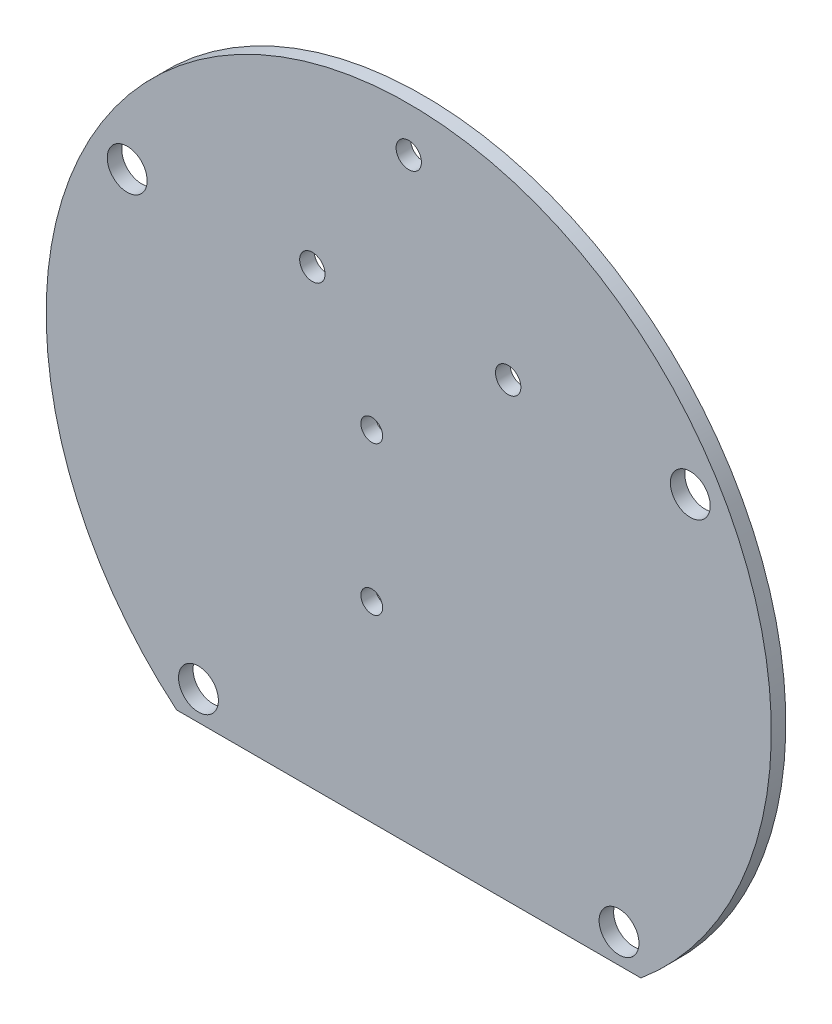
SolidWorks part; units mm, degrees
ref_plane "Plano frontal" through (0, 0, 0) normal (0, 0, 1) x (1, 0, 0)
ref_plane "Plano superior" through (0, 0, 0) normal (0, 1, 0) x (1, 0, 0)
ref_plane "Plano direito" through (0, 0, 0) normal (1, 0, 0) x (0, 0, -1)
sketch "Esboço1" plane through (0, 0, 0) normal (0, 0, 1) x (1, 0, 0)
  circle A0 centre (0, 0) radius 50
  dimension "D1" = 100
extrude "Ressalto-extrusão1" add sketch "Esboço1" along normal blind 2
sketch "Esboço2" plane through (0, 0, 2) normal (0, 0, 1) x (1, 0, 0)
  line L0 (0, 0) -> (0, 68.6386) construction
  line L1 (-61.9657, 0) -> (66.0984, 0) construction
  line L2 (-61.9657, -34.4093) -> (66.0984, -34.4093) construction
  circle A4 centre (-29, -34.4093) radius 2.75
  circle A5 centre (29, -34.4093) radius 2.75
  circle A6 centre (-38.8242, 22.7526) radius 2.75
  circle A7 centre (38.8242, 22.7526) radius 2.75
  point P9 (2.9328, -3.8481)
  dimension "D1" = 58
  dimension "D4" = 45
  dimension "D2" = 45
  dimension "D8" = 5.5
  dimension "D9" = 5.5
  dimension "D10" = 5.5
  dimension "D11" = 5.5
  dimension "D3" = 45
  dimension "D5" = 45
  dimension "D6" = 58
  dimension "D7" = 58
extrude "Corte-extrusão1" cut sketch "Esboço2" against normal blind 2
sketch "Esboço4" plane through (0, 0, 2) normal (0, 0, 1) x (1, 0, 0)
  line L0 (-40.7239, -38.4093) -> (44.5707, -38.4093)
  line L1 (-40.7239, -38.4093) -> (1.9234, -68.0022)
  line L2 (1.9234, -68.0022) -> (44.5707, -38.4093)
  circle A0 centre (-29, -34.4093) radius 2.75 construction
  dimension "D1" = 4
extrude "Corte-extrusão2" cut sketch "Esboço4" against normal blind 10 and the other way through all
sketch "Esboço5" plane through (0, 0, 0) normal (0, 0, -1) x (-1, 0, 0)
  line L0 (64.3082, 0) -> (-64.3082, 0) construction
  line L1 (0, 62.8144) -> (0, -62.8144) construction
  circle A1 centre (5.1, 8.5) radius 1.5
  circle A2 centre (5.1, -12) radius 1.5
  circle A3 centre (-13.71, 23.86) radius 1.75
  circle A4 centre (13.29, 23.86) radius 1.75
  circle A5 centre (0, 43.86) radius 1.75
  point P6 (0, 0)
  point P9 (0, 0)
  dimension "D1" = 5.1
  dimension "D5" = 23.86
  dimension "D2" = 5.1
  dimension "D3" = 12
  dimension "D4" = 8.5
  dimension "D6" = 13.71
  dimension "D7" = 13.29
  dimension "D8" = 23.86
  dimension "D9" = 43.86
extrude "Corte-extrusão3" cut sketch "Esboço5" against normal blind 10
